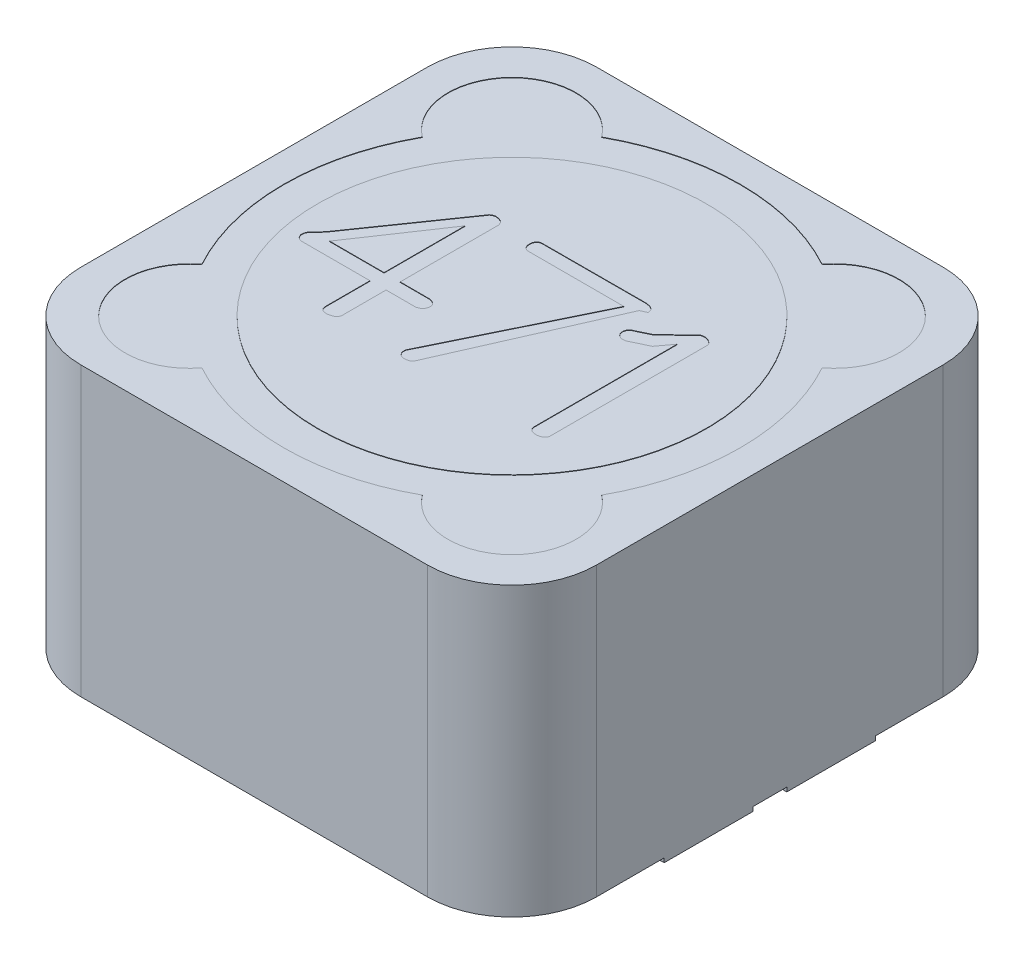
SolidWorks part; units mm, degrees
ref_plane "Front Plane" through (0, 0, 0) normal (0, 0, 1) x (1, 0, 0)
ref_plane "Top Plane" through (0, 0, 0) normal (0, 1, 0) x (1, 0, 0)
ref_plane "Right Plane" through (0, 0, 0) normal (1, 0, 0) x (0, 0, -1)
sketch "Sketch1" plane through (0, 0, 0) normal (0, 1, 0) x (1, 0, 0)
  line L5 (-4.1, 6.1) -> (4.1, 6.1)
  line L6 (-6.1, 4.1) -> (-6.1, -4.1)
  line L9 (-4.1, -6.1) -> (4.1, -6.1)
  line L16 (6.1, 4.1) -> (6.1, -4.1)
  line L17 (-6.1, 6.1) -> (6.1, -6.1) construction
  line L18 (-6.1, -6.1) -> (6.1, 6.1) construction
  arc A12 (6.1, -4.1) -> (4.1, -6.1) centre (4.1, -4.1) cw
  arc A13 (-4.1, -6.1) -> (-6.1, -4.1) centre (-4.1, -4.1) cw
  arc A14 (6.1, 4.1) -> (4.1, 6.1) centre (4.1, 4.1) ccw
  arc A15 (-6.1, 4.1) -> (-4.1, 6.1) centre (-4.1, 4.1) cw
  point P0 (0, 0)
  dimension "D2" = 2
  dimension "D1" = 12.2
extrude "Boss-Extrude1" add sketch "Sketch1" along normal blind 6.8
sketch "Sketch4" plane through (0, 0, 0) normal (0, -1, 0) x (1, 0, 0)
  line L1 (-6.1, 0.4) -> (-5.3, 0.4)
  line L2 (-5.3, 0.4) -> (-5.3, -0.4)
  line L3 (0, 6.1) -> (0, 0) construction
  line L5 (-5.3, -0.4) -> (-6.1, -0.4)
  line L6 (-6.1, 0.4) -> (-6.1, 0) construction
  line L7 (-6.1, -0.4) -> (-6.1, -2.5)
  line L8 (-5.3, 0) -> (-6.1, 0) construction
  line L24 (-4.1, 6.1) -> (4.1, 6.1) construction
  line L25 (4.1, -6.1) -> (-4.1, -6.1) construction
  line L26 (-0.85, 4.9272) -> (-0.85, 0.8)
  line L27 (-0.85, 0.8) -> (-1.8, 0.8)
  line L28 (-1.8, 0.8) -> (-1.8, -0.8)
  line L29 (-1.8, -0.8) -> (-0.85, -0.8)
  line L30 (-0.85, -0.8) -> (-0.85, -4.9272)
  line L31 (-1.8, 0) -> (0, 0) construction
  line L32 (-4.3301, 2.5) -> (-6.1, 2.5)
  line L33 (-6.1, -4.1) -> (-6.1, 4.1) construction
  line L34 (0, 0) -> (-5, 0) construction
  line L35 (-4.3301, -2.5) -> (-6.1, -2.5)
  line L36 (-6.1, 2.5) -> (-6.1, 0.4)
  line L37 (-5, 0) -> (-5.3, 0) construction
  line L38 (-6.1, 0) -> (-8.2393, 0) construction
  line L39 (0, 0) -> (0, -5) construction
  line L40 (0, -5) -> (0, -6.1) construction
  line L41 (-6.1, 0) -> (-6.1, -0.4) construction
  line L42 (0.85, 4.9272) -> (0.85, 0.8)
  line L43 (0.85, 0.8) -> (1.8, 0.8)
  line L44 (1.8, 0.8) -> (1.8, -0.8)
  line L45 (1.8, -0.8) -> (0.85, -0.8)
  line L46 (0.85, -0.8) -> (0.85, -4.9272)
  line L47 (4.3301, -2.5) -> (6.1, -2.5)
  line L48 (6.1, -0.4) -> (6.1, -2.5)
  line L49 (5.3, -0.4) -> (6.1, -0.4)
  line L50 (5.3, 0.4) -> (5.3, -0.4)
  line L51 (6.1, 0.4) -> (5.3, 0.4)
  line L52 (6.1, 2.5) -> (6.1, 0.4)
  line L53 (4.3301, 2.5) -> (6.1, 2.5)
  arc A18 (-4.3301, -2.5) -> (-0.85, -4.9272) centre (0, 0) ccw
  arc A19 (-4.3301, 2.5) -> (-5, 0) centre (0, 0) ccw construction
  arc A20 (-5, 0) -> (-4.3301, -2.5) centre (0, 0) ccw construction
  arc A21 (0, 5) -> (-0.85, 4.9272) centre (0, 0) ccw construction
  arc A22 (-0.85, 4.9272) -> (-4.3301, 2.5) centre (0, 0) ccw
  arc A23 (-0.85, -4.9272) -> (0, -5) centre (0, 0) ccw construction
  arc A24 (0, -5) -> (0, 5) centre (0, 0) ccw construction
  arc A25 (0.85, 4.9272) -> (4.3301, 2.5) centre (0, 0) cw
  arc A26 (4.3301, -2.5) -> (0.85, -4.9272) centre (0, 0) cw
  dimension "D2" = 10
  dimension "D1" = 0.85
  dimension "D3" = 3.6
  dimension "D4" = 1.6
  dimension "D5" = 5
  dimension "D6" = 0.8
  dimension "D7" = 0.8
extrude "Boss-Extrude3" add sketch "Sketch4" along normal blind 0.1
sketch "Sketch5" plane through (0, 0, 0) normal (0, 1, 0) x (1, 0, 0)
  line L0 (0, 0) -> (0, 9.8245) construction
  line L1 (0, 0) -> (9.8181, 9.8181) construction
  arc A0 (0, 5) -> (3.5355, 3.5355) centre (0, 0) ccw construction
  arc A1 (2.6074, 4.7288) -> (-2.6074, 4.7288) centre (0, 0) ccw
  circle A2 centre (0, 0) radius 4.6
  arc A3 (6.1, 4.1) -> (4.1, 6.1) centre (4.1, 4.1) ccw construction
  arc A4 (2.6074, 4.7288) -> (4.7288, 2.6074) centre (3.8184, 3.8184) cw
  arc A5 (3.8184, 3.8184) -> (2.6074, 4.7288) centre (0, 0) ccw construction
  circle A6 centre (0, 0) radius 5.4 construction
  arc A7 (3.5355, 3.5355) -> (0, 5) centre (0, 0) ccw construction
  circle A8 centre (0, 0) radius 5 construction
  arc A9 (4.7288, 2.6074) -> (3.8184, 3.8184) centre (0, 0) ccw construction
  arc A10 (4.7288, -2.6074) -> (2.6074, -4.7288) centre (3.8184, -3.8184) cw
  arc A11 (-2.6074, -4.7288) -> (-4.7288, -2.6074) centre (-3.8184, -3.8184) cw
  arc A12 (-4.7288, 2.6074) -> (-2.6074, 4.7288) centre (-3.8184, 3.8184) cw
  arc A13 (-2.6074, 4.7288) -> (-4.7288, 2.6074) centre (0, 0) ccw construction
  arc A14 (-4.7288, 2.6074) -> (-4.7288, -2.6074) centre (0, 0) ccw
  arc A15 (-4.7288, -2.6074) -> (-2.6074, -4.7288) centre (0, 0) ccw construction
  arc A16 (-2.6074, -4.7288) -> (2.6074, -4.7288) centre (0, 0) ccw
  arc A17 (2.6074, -4.7288) -> (4.7288, -2.6074) centre (0, 0) ccw construction
  arc A18 (4.7288, -2.6074) -> (4.7288, 2.6074) centre (0, 0) ccw
  point P12 (5.5142, 5.5142)
  point P30 (0, 0)
  dimension "D1" = 10
  dimension "D4" = 3
  dimension "D2" = 0.4
  dimension "D3" = 0.4
  dimension "D5" = 4
extrude "Cut-Extrude1" cut sketch "Sketch5" against normal blind 0.01 from surface at 6.8 starting at face at (0, 6.8, 0)
sketch "Sketch6" plane through (0, 0, 0) normal (0, 1, 0) x (1, 0, 0)
  line L0 (-4.1172, -2.0515) -> (4.1172, -2.0515) construction
  circle A0 centre (0, 0) radius 4.6 construction
  text T0 "471" font "SWSimp" height 4
extrude "Cut-Extrude2" cut sketch "Sketch6" against normal blind 0.01 from surface at 6.8 starting at face at (0, 6.8, -4.6)
